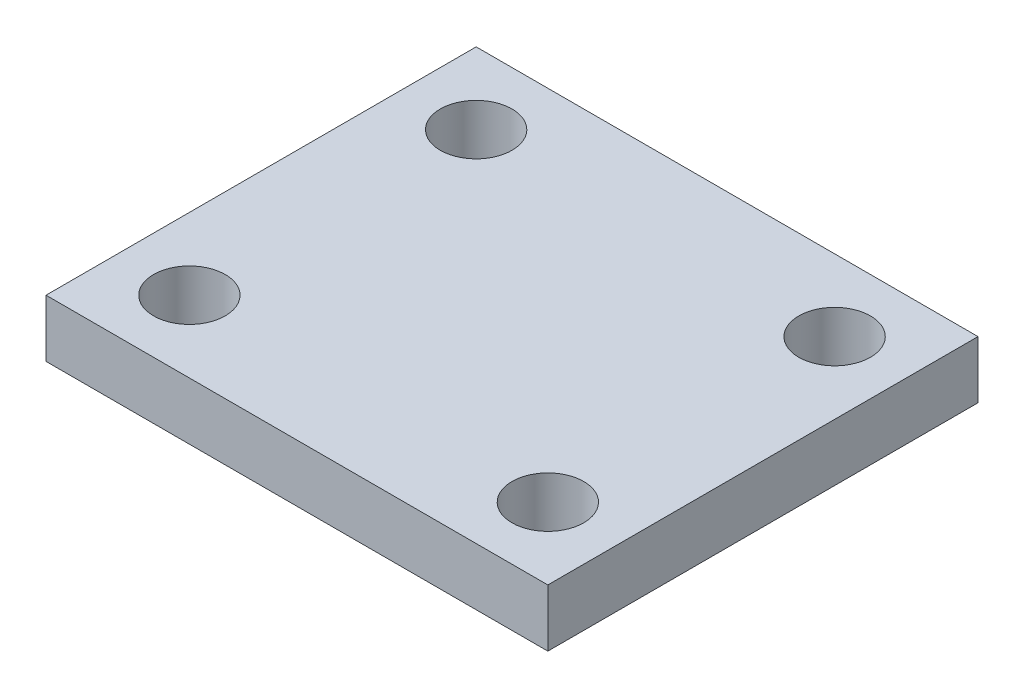
SolidWorks part; units mm, degrees
ref_plane "Front Plane" through (0, 0, 0) normal (0, 0, 1) x (1, 0, 0)
ref_plane "Top Plane" through (0, 0, 0) normal (0, 1, 0) x (1, 0, 0)
ref_plane "Right Plane" through (0, 0, 0) normal (1, 0, 0) x (0, 0, -1)
sketch "Sketch1" plane through (0, 0, 0) normal (0, 1, 0) x (1, 0, 0)
  line L1 (0, 0) -> (35, 0)
  line L2 (0, 0) -> (0, 30)
  line L3 (0, 30) -> (35, 30)
  line L4 (35, 0) -> (35, 30)
  circle A0 centre (5, 25) radius 2.5
  circle A4 centre (30, 25) radius 2.5
  circle A5 centre (5, 5) radius 2.5
  circle A6 centre (30, 5) radius 2.5
  dimension "D3" = 5
  dimension "D1" = 30
  dimension "D2" = 35
  dimension "D4" = 5
  dimension "5" = 5
  dimension "D5" = 5
  dimension "D6" = 5
  dimension "D7" = 5
  dimension "D8" = 5
  dimension "D9" = 5
  dimension "D10" = 5
extrude "Boss-Extrude1" add sketch "Sketch1" along normal blind 4
